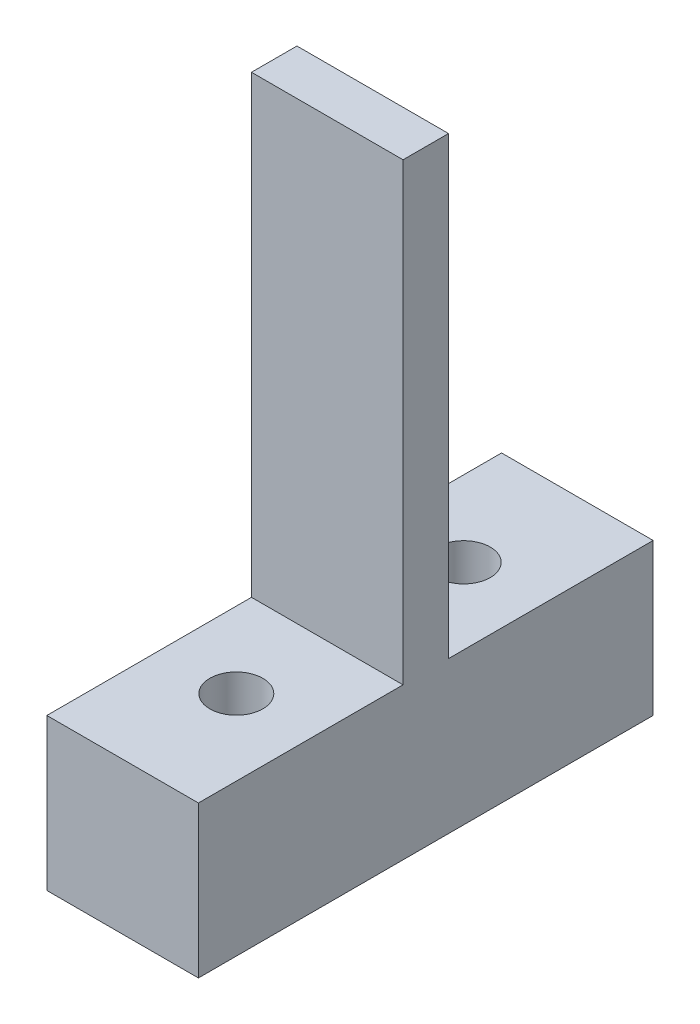
SolidWorks part; units mm, degrees
ref_plane "Front Plane" through (0, 0, 0) normal (0, 0, 1) x (1, 0, 0)
ref_plane "Top Plane" through (0, 0, 0) normal (0, 1, 0) x (1, 0, 0)
ref_plane "Right Plane" through (0, 0, 0) normal (1, 0, 0) x (0, 0, -1)
sketch "Sketch2" plane through (0, 0, 0) normal (0, 1, 0) x (1, 0, 0)
  line L0 (-46.876, 20.8745) -> (-46.876, -9.1255) construction
  line L1 (-46.876, 20.8745) -> (-36.876, 20.8745)
  line L2 (-36.876, 20.8745) -> (-36.876, -9.1255)
  line L3 (-36.876, -9.1255) -> (-46.876, -9.1255)
  line L4 (-41.876, 20.8745) -> (-41.876, -9.1255) construction
  line L5 (-41.876, -9.1255) -> (-41.876, 5.8745) construction
  line L6 (-41.876, 5.8745) -> (-46.876, 5.8745) construction
  line L7 (-46.876, 5.8745) -> (-36.876, 5.8745) construction
  line L8 (-36.876, 5.8745) -> (-41.876, 5.8745) construction
  line L9 (-41.876, 5.8745) -> (-41.876, 20.8745) construction
  line L19 (-46.876, -9.1255) -> (-46.876, 20.8745)
  circle A0 centre (-41.876, -1.6255) radius 1.75
  circle A1 centre (-41.876, 13.3745) radius 1.75
extrude "Boss-Extrude1" add sketch "Sketch2" along normal blind 10
sketch "Sketch4" plane through (0, 10, 0) normal (0, 1, 0) x (1, 0, 0)
  line L0 (-46.876, 5.8745) -> (-36.876, 5.8745) construction
  line L1 (-46.876, 20.8745) -> (-46.876, -9.1255) construction
  line L2 (-36.876, -9.1255) -> (-36.876, 20.8745) construction
  line L3 (-46.876, 5.8745) -> (-46.876, 7.3745)
  line L4 (-46.876, 7.3745) -> (-46.876, 4.3745)
  line L5 (-46.876, 4.3745) -> (-36.876, 4.3745)
  line L6 (-36.876, 4.3745) -> (-36.876, 7.3745)
  line L7 (-36.876, 7.3745) -> (-46.876, 7.3745)
  line M1 (-46.876, 20.8745) -> (-46.876, -9.1255)
  line M3 (-36.876, -9.1255) -> (-36.876, 20.8745)
extrude "Boss-Extrude3" add sketch "Sketch4" along normal blind 30 contours L0 L6 L7 M1 | L0 L5 M1 M3
